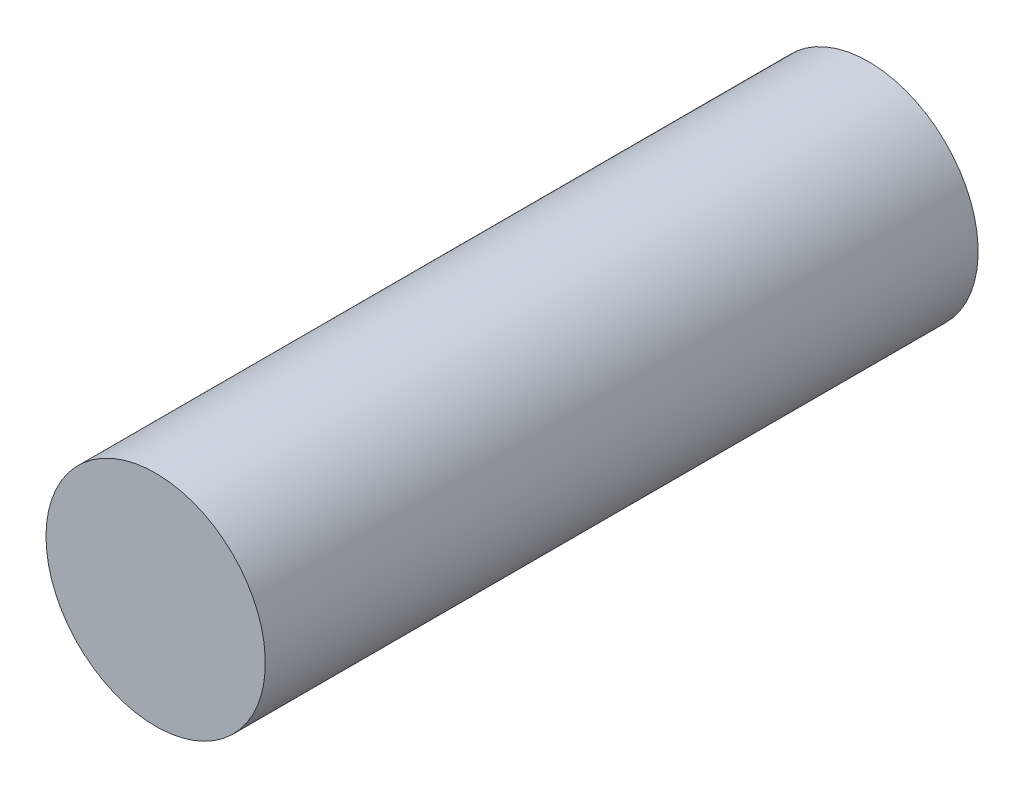
SolidWorks part; units mm, degrees
ref_plane "Piano frontale" through (0, 0, 0) normal (0, 0, 1) x (1, 0, 0)
ref_plane "Piano superiore" through (0, 0, 0) normal (0, 1, 0) x (1, 0, 0)
ref_plane "Piano destro" through (0, 0, 0) normal (1, 0, 0) x (0, 0, -1)
sketch "Schizzo1" plane through (0, 0, 0) normal (0, 0, 1) x (1, 0, 0)
  circle A0 centre (0, 0) radius 2
  dimension "D1" = 4
extrude "Estrusione-Estrusione1" add sketch "Schizzo1" along normal blind 13
